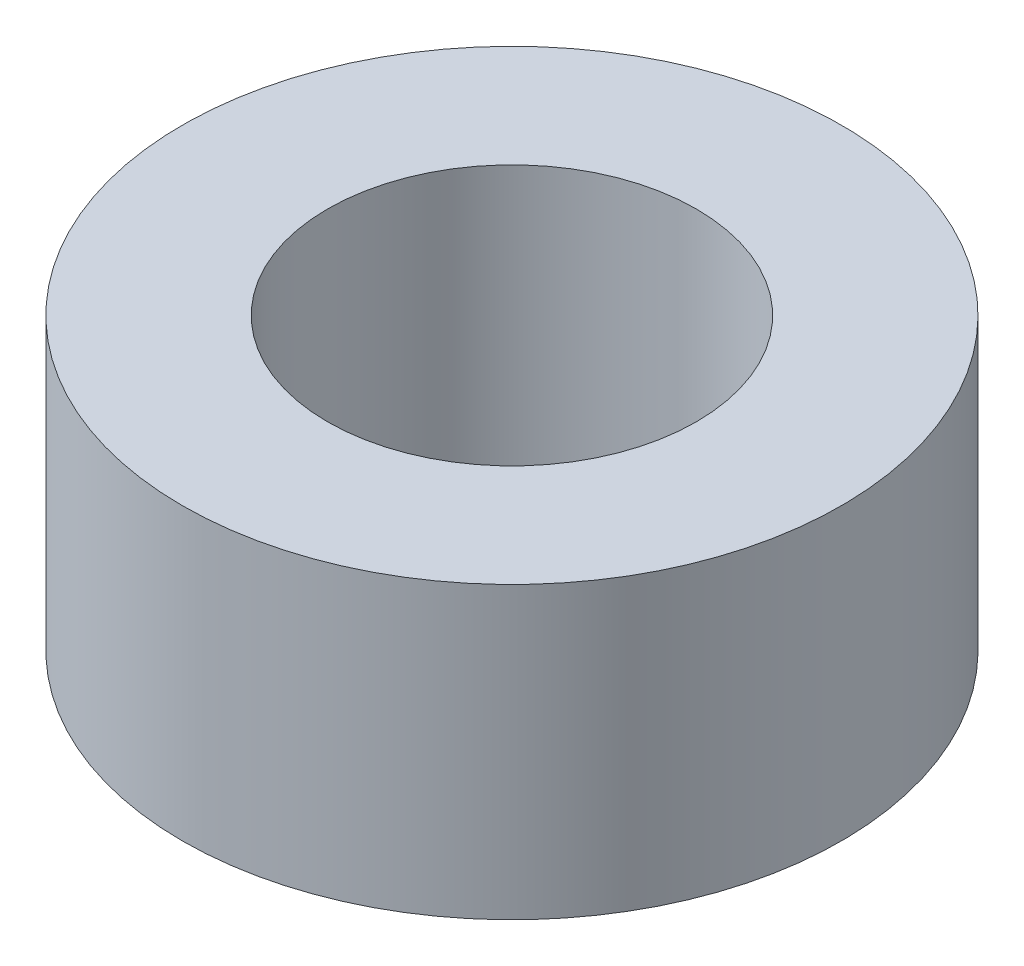
SolidWorks part; units mm, degrees
ref_plane "Спереди (XY)" through (0, 0, 0) normal (0, 0, 1) x (1, 0, 0)
ref_plane "Сверху (XZ)" through (0, 0, 0) normal (0, 1, 0) x (1, 0, 0)
ref_plane "Справа (ZY)" through (0, 0, 0) normal (1, 0, 0) x (0, 0, -1)
sketch "Эскиз2" plane through (0, 0, 0) normal (0, 1, 0) x (1, 0, 0)
  circle A0 centre (0, 0) radius 12.7
  circle A1 centre (0, 0) radius 22.7
  dimension "D1" = 25.4
  dimension "D2" = 10
extrude "Бобышка-Вытянуть1" add sketch "Эскиз2" along normal mid plane 20
sketch "Эскиз3" plane through (0, 0, 0) normal (1, 0, 0) x (0, 0, -1)
  line L1 (5.7735, 0) -> (2.8868, 5)
  line L2 (2.8868, 5) -> (-2.8868, 5)
  line L3 (-2.8868, 5) -> (-5.7735, 0)
  line L4 (-5.7735, 0) -> (-2.8868, -5)
  line L5 (-2.8868, -5) -> (2.8868, -5)
  line L6 (2.8868, -5) -> (5.7735, 0)
  circle A0 centre (0, 0) radius 5 construction
  dimension "D1" = 10
extrude "Бобышка-Вытянуть2" add sketch "Эскиз3" against normal blind 5 from offset 20 offset against normal yes
sketch "Эскиз4" plane through (-25, 0, 0) normal (-1, 0, 0) x (0, 0, 1)
  circle A0 centre (0, 0) radius 4
  dimension "D1" = 8
extrude "Вырез-Вытянуть2" cut sketch "Эскиз4" against normal blind 5
